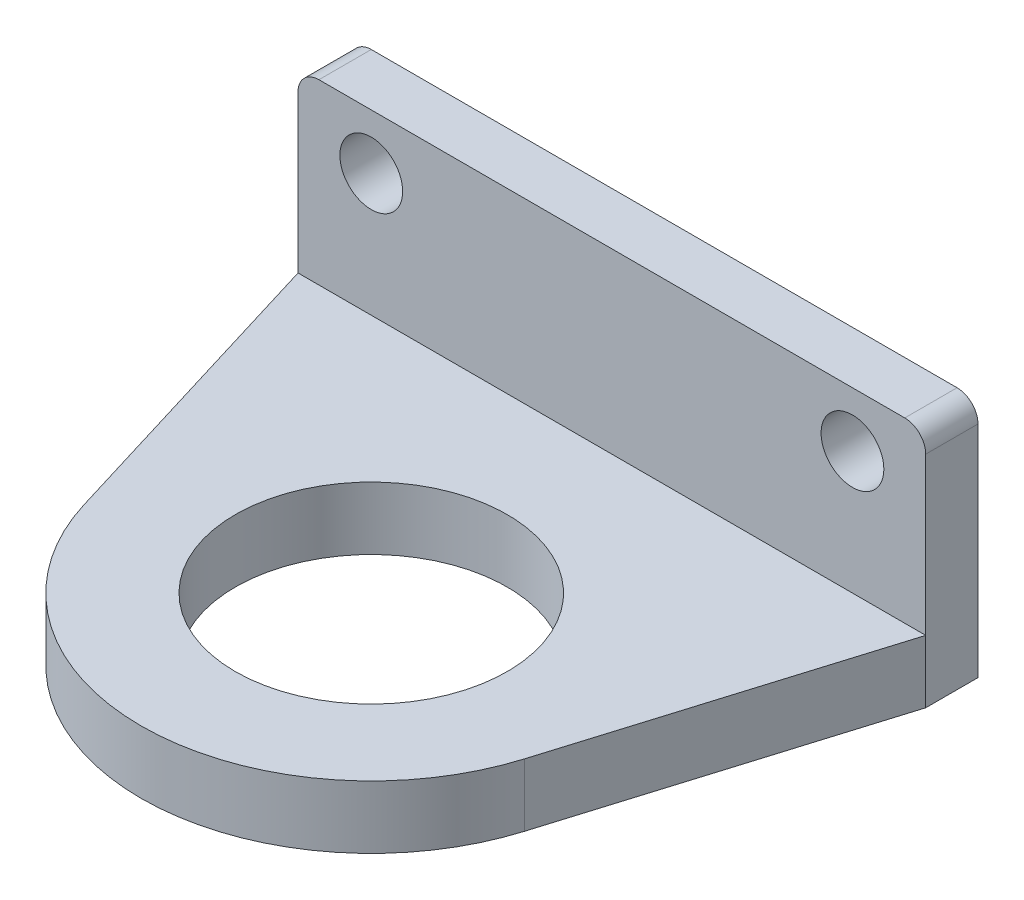
SolidWorks part; units mm, degrees
ref_plane "Front Plane" through (0, 0, 0) normal (0, 0, 1) x (1, 0, 0)
ref_plane "Top Plane" through (0, 0, 0) normal (0, 1, 0) x (1, 0, 0)
ref_plane "Right Plane" through (0, 0, 0) normal (1, 0, 0) x (0, 0, -1)
sketch "Sketch1" plane through (0, 0, 0) normal (0, 1, 0) x (1, 0, 0)
  line L0 (0, -7.5) -> (-15, -7.5) construction
  line L1 (-15, 0) -> (15, 0)
  line L2 (-15, 0) -> (-15, -2.5)
  line L4 (15, 0) -> (15, -2.5)
  line L5 (-15, -2.5) -> (15, -2.5) construction
  line L6 (-15, -2.5) -> (-10.523, -17.204)
  line L7 (15, -2.5) -> (10.523, -17.204)
  line L8 (0, -14) -> (0, -7.5) construction
  circle A0 centre (0, -14) radius 6.5
  arc A1 (-10.523, -17.204) -> (10.523, -17.204) centre (0, -14) ccw
  point P9 (15.7948, -2.5)
  dimension "D2" = 4.5
  dimension "D3" = 13
  dimension "D4" = 7.5
  dimension "D1" = 14
  dimension "D5" = 2.5
  dimension "D6" = 30
extrude "Boss-Extrude1" add sketch "Sketch1" against normal blind 3
sketch "Sketch2" plane through (0, 0, 0) normal (0, 1, 0) x (1, 0, 0)
  line L0 (15, 0) -> (15, -2.5) construction
  line L1 (-15, 0) -> (15, 0) construction
  line L2 (-15, 0) -> (-15, -2.5) construction
  line L3 (-15, -2.5) -> (15, -2.5) construction
  line L4 (15, 0) -> (15, -2.5)
  line L5 (-15, 0) -> (15, 0)
  line L6 (-15, 0) -> (-15, -2.5)
  line L7 (-15, -2.5) -> (15, -2.5)
extrude "Boss-Extrude2" add sketch "Sketch2" along normal blind 8.5
fillet "Fillet1" radius 1 2 edges at (15, 8.5, 1.25) (-15, 8.5, 1.25)
sketch "Sketch3" plane through (0, 0, 2.5) normal (0, 0, 1) x (1, 0, 0)
  line L0 (0, 0) -> (0, 5.8746) construction
  line L1 (-15, 0) -> (15, 0) construction
  line L2 (0, 5.8746) -> (11.5, 5.8746) construction
  circle A0 centre (11.5, 5.8746) radius 1.5
  dimension "D3" = 3
  dimension "D1" = 5.8746
  dimension "D2" = 11.5
extrude "Cut-Extrude1" cut sketch "Sketch3" against normal blind 8.5
mirror "Mirror1" about plane through (0, 0, 0) normal (1, 0, 0) of "Cut-Extrude1"
